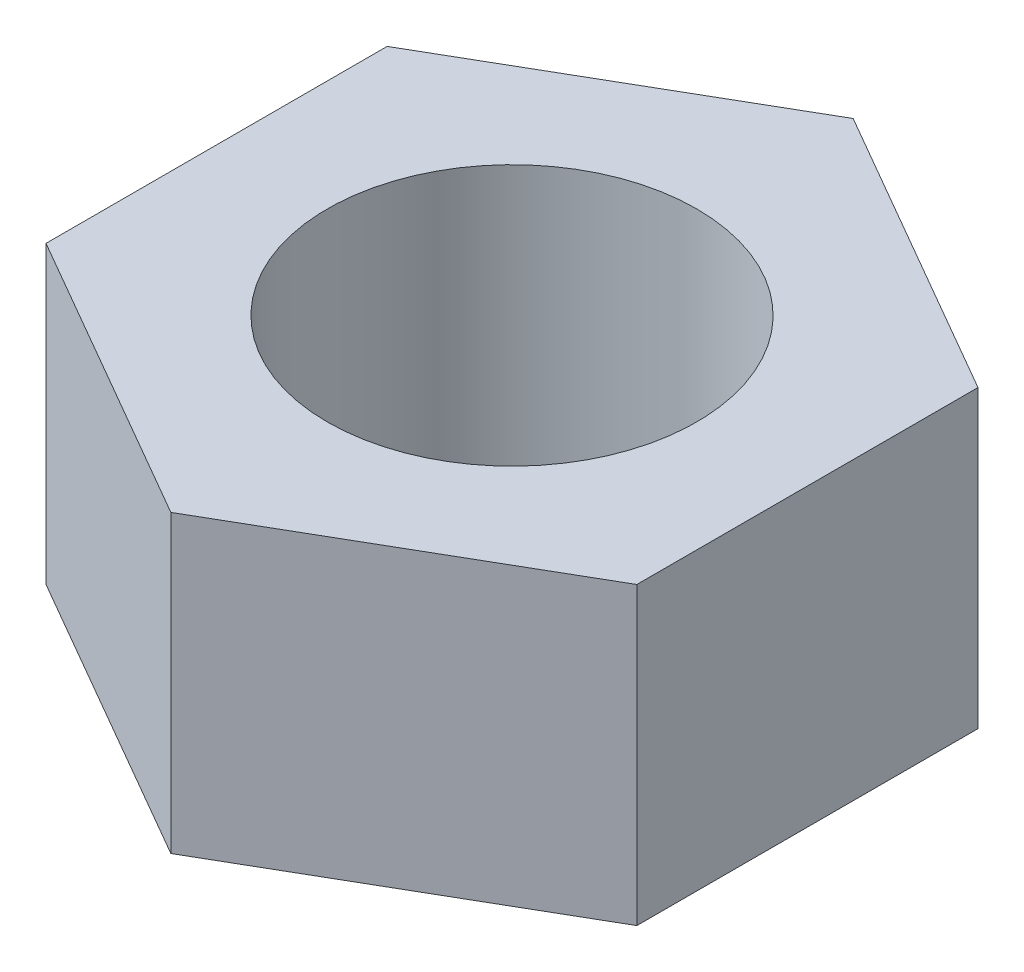
SolidWorks part; units mm, degrees
material "AISI 304"
ref_plane "前视基准面" through (0, 0, 0) normal (0, 0, 1) x (1, 0, 0)
ref_plane "上视基准面" through (0, 0, 0) normal (0, 1, 0) x (1, 0, 0)
ref_plane "右视基准面" through (0, 0, 0) normal (1, 0, 0) x (0, 0, -1)
sketch "草图1" plane through (0, 0, 0) normal (0, 1, 0) x (1, 0, 0)
  line L1 (0, 4.6188) -> (-4, 2.3094)
  line L2 (-4, 2.3094) -> (-4, -2.3094)
  line L3 (-4, -2.3094) -> (0, -4.6188)
  line L4 (0, -4.6188) -> (4, -2.3094)
  line L5 (4, -2.3094) -> (4, 2.3094)
  line L6 (4, 2.3094) -> (0, 4.6188)
  circle A0 centre (0, 0) radius 2.5
  circle A1 centre (0, 0) radius 4 construction
  dimension "D1" = 5
  dimension "D2" = 8
extrude "凸台-拉伸1" add sketch "草图1" along normal blind 4
equation "\"内径\"= 5"
equation "\"厚\"= 4"
equation "\"宽\"= 8"
equation "\"D1@草图1\"= \"内径\""
equation "\"D2@草图1\"= \"宽\""
equation "\"D1@凸台-拉伸1\"= \"厚\""
